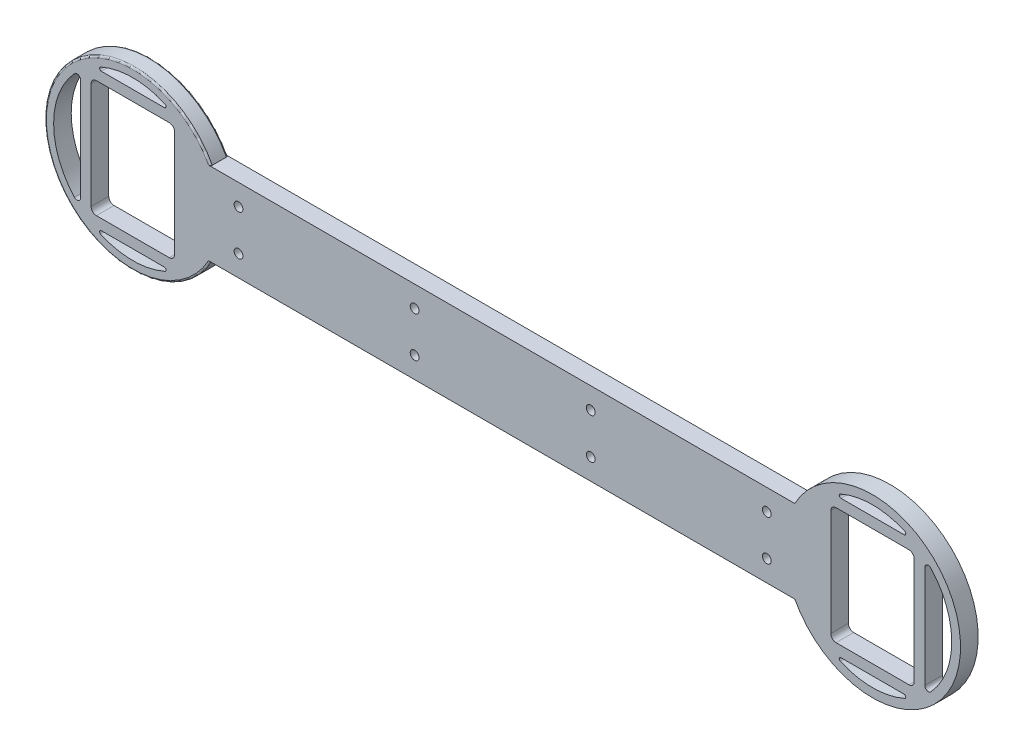
SolidWorks part; units mm, degrees
ref_plane "前视基准面" through (0, 0, 0) normal (0, 0, 1) x (1, 0, 0)
ref_plane "上视基准面" through (0, 0, 0) normal (0, 1, 0) x (1, 0, 0)
ref_plane "右视基准面" through (0, 0, 0) normal (1, 0, 0) x (0, 0, -1)
sketch "草图1" plane through (0, 0, 0) normal (0, 0, 1) x (1, 0, 0)
  line L0 (0, -114.9603) -> (0, 164.1005) construction
  line L1 (-210, -23.5) -> (0, -23.5)
  line L2 (-210, 23.5) -> (0, 23.5)
  line L3 (-210, 0) -> (-210, 65.4164) construction
  line L4 (-210, 0) -> (-106.141, 0) construction
  line L5 (-233.7, -33.2) -> (-233.7, 33.2)
  line L6 (-233.7, 33.2) -> (-186.3, 33.2)
  line L7 (-186.3, -33.2) -> (-186.3, 33.2)
  line L8 (-233.7, -33.2) -> (-186.3, -33.2)
  line L9 (-239.7, 0) -> (-239.7, 50.4262) construction
  line L10 (-239.7, 33.807) -> (-239.7, -33.807)
  line L11 (-180.3, 33.807) -> (-180.3, -33.807)
  line L12 (-210, 39.2) -> (-130.0604, 39.2) construction
  line L13 (-232.0989, 39.2) -> (-187.9011, 39.2)
  line L14 (-232.0989, -39.2) -> (-187.9011, -39.2)
  line L15 (0, 23.5) -> (0, -23.5)
  circle A0 centre (-210, 0) radius 23.5
  circle A1 centre (-210, 0) radius 50
  arc A2 (-239.7, -33.807) -> (-239.7, 33.807) centre (-210, 0) cw
  arc A3 (-180.3, -33.807) -> (-180.3, 33.807) centre (-210, 0) ccw
  arc A4 (-232.0989, 39.2) -> (-187.9011, 39.2) centre (-210, 0) cw
  arc A5 (-232.0989, -39.2) -> (-187.9011, -39.2) centre (-210, 0) ccw
  circle A6 centre (-150, 11.5) radius 2.5
  circle A7 centre (-150, -11.5) radius 2.5
  circle A8 centre (-50, 11.5) radius 2.5
  circle A9 centre (-50, -11.5) radius 2.5
  point P17 (-210, 33.2)
  point P19 (-186.3, 0)
  point P20 (-233.7, 0)
  point P37 (0, 0)
  point P41 (-17.1528, 12.771)
  dimension "D2" = 47
  dimension "D5" = 6
  dimension "D6" = 6
  dimension "D7" = 12
  dimension "D9" = 50
  dimension "D1" = 210
  dimension "D3" = 33.2
  dimension "D4" = 23.7
  dimension "D8" = 150
  dimension "D10" = 12
extrude "凸台-拉伸1" add sketch "草图1" along normal blind 10 contours A1 L1 L15 L2 | A3 L1 A1 L2 | A3 L2 A1 L1 L11 L7 L8 L5 L6 A5 L14 L10 A2 L13 A4 | L11 L2 L7 L1
fillet "圆角1" radius 3 4 edges at (-233.7, -33.2, 5) (-186.3, -33.2, 5) (-186.3, 33.2, 5) (-233.7, 33.2, 5)
fillet "圆角2" radius 2 2 edges at (-239.7, 33.807, 5) (-239.7, -33.807, 5)
fillet "圆角3" [suppressed] radius 2
fillet "圆角4" radius 1 4 edges at (-232.0989, -39.2, 5) (-187.9011, -39.2, 5) (-187.9011, 39.2, 5) (-232.0989, 39.2, 5)
fillet "圆角5" radius 1 2 edges at (-260, 0, 0) (-260, 0, 10)
mirror "镜向1" about plane through (0, 0, 10) normal (1, 0, 0) of "圆角2", "圆角3", "圆角1", "圆角4", "凸台-拉伸1"
